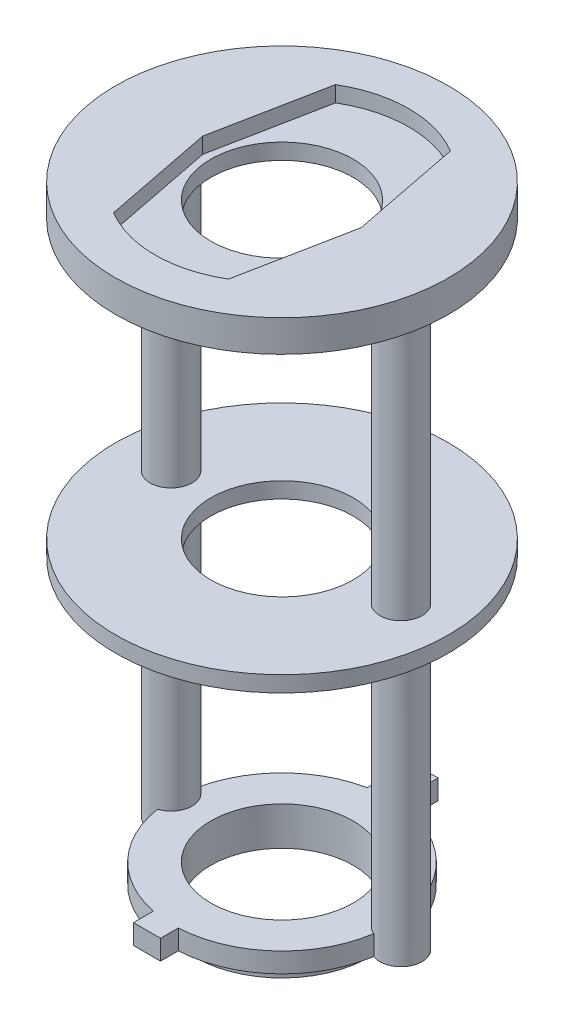
SolidWorks part; units mm, degrees
material "ABS"
ref_plane "Front Plane" through (0, 0, 0) normal (0, 0, 1) x (1, 0, 0)
ref_plane "Top Plane" through (0, 0, 0) normal (0, 1, 0) x (1, 0, 0)
ref_plane "Right Plane" through (0, 0, 0) normal (1, 0, 0) x (0, 0, -1)
sketch "Sketch1" plane through (0, 0, 0) normal (0, 1, 0) x (1, 0, 0)
  line L0 (14.5034, -1.0795) -> (-14.5034, -1.0795) construction
  line L1 (0.598, 12.2364) -> (0.598, 17.5133)
  line L2 (0.598, 17.5133) -> (-2.8194, 17.5133)
  line L3 (-2.8194, 17.5133) -> (-2.8194, 11.9769)
  line L4 (-2.8194, -15.0046) -> (-2.8194, -17.5133)
  line L5 (-2.8194, -17.5133) -> (0.598, -17.5133)
  line L6 (0.598, -17.5133) -> (0.598, -15.2641)
  arc A0 (-2.8194, 11.9769) -> (-13.533, 1.3911) centre (-0.0762, -1.5138) ccw
  arc A1 (-13.533, 1.3911) -> (-13.6834, -3.604) centre (-14.5034, -1.0795) ccw
  arc A2 (-13.6834, -3.604) -> (-2.8194, -15.0046) centre (-0.0762, -1.5138) ccw
  arc A3 (0.598, -15.2641) -> (13.5388, -3.5523) centre (-0.0762, -1.5138) ccw
  arc A4 (13.5388, -3.5523) -> (13.3933, 1.3315) centre (14.5034, -1.0795) ccw
  arc A5 (13.3933, 1.3315) -> (0.598, 12.2364) centre (-0.0762, -1.5138) ccw
  dimension "D1" = 13.7668
  dimension "D2" = 2.6543
  dimension "D6" = 13.7668
  dimension "D15" = 2.6543
  dimension "D3" = 2.5087
  dimension "D4" = 2.2492
  dimension "D5" = 3.4174
  dimension "D7" = 14.5796
  dimension "D8" = 14.4272
  dimension "D9" = 5.2769
  dimension "D10" = 5.5364
  dimension "D11" = 3.4174
  dimension "D12" = 0.6742
  dimension "D13" = 2.7432
  dimension "D14" = 0.4343
extrude "Boss-Extrude1" add sketch "Sketch1" along normal blind 2.5
sketch "Sketch2" plane through (0, 2.5, 0) normal (0, 1, 0) x (1, 0, 0)
  circle A1 centre (-14.5034, -1.0795) radius 1.715
  circle A2 centre (14.5034, -1.0795) radius 1.715
  circle A3 centre (-0.0762, -1.5138) radius 8.98
  dimension "D1" = 3.43
  dimension "D2" = 3.43
  dimension "D3" = 17.96
extrude "Cut-Extrude1" cut sketch "Sketch2" against normal up to next contours A1 | A2 | A3
sketch "Sketch3" plane through (0, 2.5, 0) normal (0, 1, 0) x (1, 0, 0)
  circle A0 centre (-14.5034, -1.0795) radius 2.6543
  circle A1 centre (14.5034, -1.0795) radius 2.6543
extrude "Boss-Extrude2" add sketch "Sketch3" along normal blind 70.305
sketch "Sketch4" plane through (0, 72.805, 0) normal (0, 1, 0) x (1, 0, 0)
  circle A0 centre (-0.0762, -1.5138) radius 8.98
  circle A1 centre (-0.0762, -1.5138) radius 21
  dimension "D1" = 42
extrude "Boss-Extrude3" add sketch "Sketch4" along normal blind 4
sketch "Sketch5" plane through (0, 76.805, 0) normal (0, 1, 0) x (1, 0, 0)
  line L0 (-0.0762, -1.5104) -> (-7.4262, -1.5104) construction
  line L1 (-7.4262, 12.1396) -> (-10.0762, -1.5104)
  line L2 (-10.0762, -1.5104) -> (-7.4262, -15.1604)
  line L3 (7.2738, -15.1604) -> (9.9238, -1.5104)
  line L4 (9.9238, -1.5104) -> (7.2738, 12.1396)
  circle A0 centre (-0.0762, -1.5104) radius 21
  arc A1 (-7.4262, 12.1396) -> (7.2738, 12.1396) centre (-0.0762, -1.5069) cw
  arc A2 (-7.4262, -15.1604) -> (7.2738, -15.1604) centre (-0.0762, -1.5138) ccw
  point P11 (-0.0762, -1.5138)
  dimension "D5" = 15.5
  dimension "D6" = 15.5
  dimension "D1" = 14.7
  dimension "D2" = 27.3
  dimension "D3" = 10
  dimension "D4" = 10
ref_plane "Plane1" through (0, 37.805, 0) normal (0, -1, 0) x (-1, 0, 0)
sketch "Sketch6" plane through (0, 37.805, 0) normal (0, -1, 0) x (-1, 0, 0)
  circle A0 centre (0.0762, -1.5138) radius 21
  circle A1 centre (0.0762, -1.5138) radius 8.98
extrude "Boss-Extrude4" add sketch "Sketch6" along normal blind 2
sketch "Sketch7" plane through (0, 0, 0) normal (0, -1, 0) x (1, 0, 0)
  circle A0 centre (-14.5034, 1.0795) radius 1.715
  circle A1 centre (14.5034, 1.0795) radius 1.715
extrude "Cut-Extrude3" cut sketch "Sketch7" against normal blind 15
sketch "Sketch8" plane through (0, 76.805, 0) normal (0, 1, 0) x (1, 0, 0)
  line L0 (-10.0762, -1.5138) -> (9.9238, -1.5138) construction
  line L1 (9.9238, -17.5138) -> (-10.0762, -17.5138) construction
  line L2 (9.9238, -17.5138) -> (9.9238, 14.4862) construction
  line L3 (9.9238, 14.4862) -> (-10.0762, 14.4862) construction
  line L4 (-10.0762, -17.5138) -> (-10.0762, 14.4862) construction
  line L5 (9.9238, -17.5138) -> (-10.0762, 14.4862) construction
  line L6 (9.9238, 14.4862) -> (-10.0762, -17.5138) construction
  line L7 (7.1738, -15.5138) -> (-7.3262, -15.5138) construction
  line L8 (7.1738, -15.5138) -> (7.1738, 12.4862) construction
  line L9 (7.1738, 12.4862) -> (-7.3262, 12.4862) construction
  line L10 (-7.3262, -15.5138) -> (-7.3262, 12.4862) construction
  line L11 (7.1738, -15.5138) -> (-7.3262, 12.4862) construction
  line L12 (7.1738, 12.4862) -> (-7.3262, -15.5138) construction
  line L13 (-10.0762, -1.5138) -> (-7.3262, -15.5138)
  line L14 (7.1738, -15.5138) -> (9.9238, -1.5138)
  line L15 (9.9238, -1.5138) -> (7.1738, 12.4862)
  line L16 (-7.3262, 12.4862) -> (-10.0762, -1.5138)
  circle A0 centre (-0.0762, -1.5138) radius 8.98
  arc A1 (-7.3262, 12.4862) -> (7.1738, 12.4862) centre (-0.0762, 0.3455) cw
  arc A2 (-7.3262, -15.5138) -> (7.1738, -15.5138) centre (-0.0762, -3.3732) ccw
  dimension "D1" = 32
  dimension "D2" = 20
  dimension "D3" = 14.5
  dimension "D4" = 28
extrude "Cut-Extrude4" cut sketch "Sketch8" against normal blind 2
sketch "Sketch9" plane through (0, 0, 0) normal (0, -1, 0) x (1, 0, 0)
  circle A0 centre (-0.0762, 1.5138) radius 8.9789
  circle A1 centre (-0.0762, 1.5138) radius 11.0744
  circle A2 centre (-0.0762, 1.5138) radius 8.98
  circle M2 centre (-0.0762, 1.5138) radius 8.98
extrude "Boss-Extrude5" add sketch "Sketch9" along normal blind 2.35 contours A1 M2
